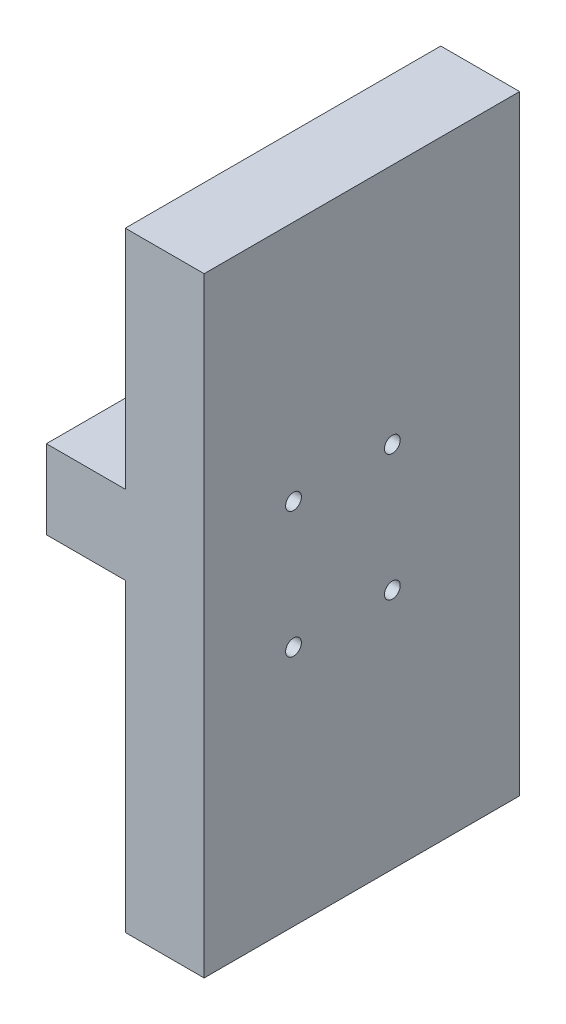
SolidWorks part; units mm, degrees
ref_plane "Alzado" through (0, 0, 0) normal (0, 0, 1) x (1, 0, 0)
ref_plane "Planta" through (0, 0, 0) normal (0, 1, 0) x (1, 0, 0)
ref_plane "Vista lateral" through (0, 0, 0) normal (1, 0, 0) x (0, 0, -1)
sketch "Croquis1" plane through (0, 0, 0) normal (1, 0, 0) x (0, 0, -1)
  line L1 (0, 0) -> (60, 0)
  line L2 (0, 0) -> (0, 116)
  line L3 (0, 116) -> (60, 116)
  line L4 (60, 0) -> (60, 116)
  dimension "D1" = 60
  dimension "D2" = 116
extrude "Saliente-Extruir1" add sketch "Croquis1" along normal blind 15
sketch "Croquis2" plane through (0, 0, 0) normal (-1, 0, 0) x (0, 0, 1)
  line L0 (-60, 58) -> (0, 58) construction
  line L1 (-60, 0) -> (-60, 116) construction
  line L2 (0, 116) -> (0, 0) construction
  line L4 (-60, 58) -> (-45, 58)
  line L5 (-60, 58) -> (-60, 43)
  line L6 (-60, 43) -> (-45, 43)
  line L7 (-45, 58) -> (-45, 43)
  line L8 (0, 58) -> (-15, 58)
  line L9 (0, 58) -> (0, 73)
  line L10 (0, 73) -> (-15, 73)
  line L11 (-15, 58) -> (-15, 73)
  dimension "D1" = 15
  dimension "D2" = 15
extrude "Saliente-Extruir2" add sketch "Croquis2" along normal blind 15
sketch "Croquis3" plane through (15, 0, 0) normal (1, 0, 0) x (0, 0, -1)
  line L0 (0, 116) -> (0, 0) construction
  line L1 (60, 116) -> (0, 116) construction
  line L3 (15.5, 71.5) -> (37.3, 71.5) construction
  line L4 (15.5, 71.5) -> (15.5, 44.5) construction
  line L5 (15.5, 44.5) -> (37.3, 44.5) construction
  line L6 (37.3, 71.5) -> (37.3, 44.5) construction
  circle A0 centre (17, 70) radius 1.5
  circle A1 centre (17, 46) radius 1.5
  circle A2 centre (35.8, 70) radius 1.5
  circle A3 centre (35.8, 46) radius 1.5
  dimension "D1" = 3
  dimension "D2" = 17
  dimension "D5" = 46
  dimension "D6" = 21.8
  dimension "D7" = 27
extrude "Cortar-Extruir1" cut sketch "Croquis3" against normal through all
